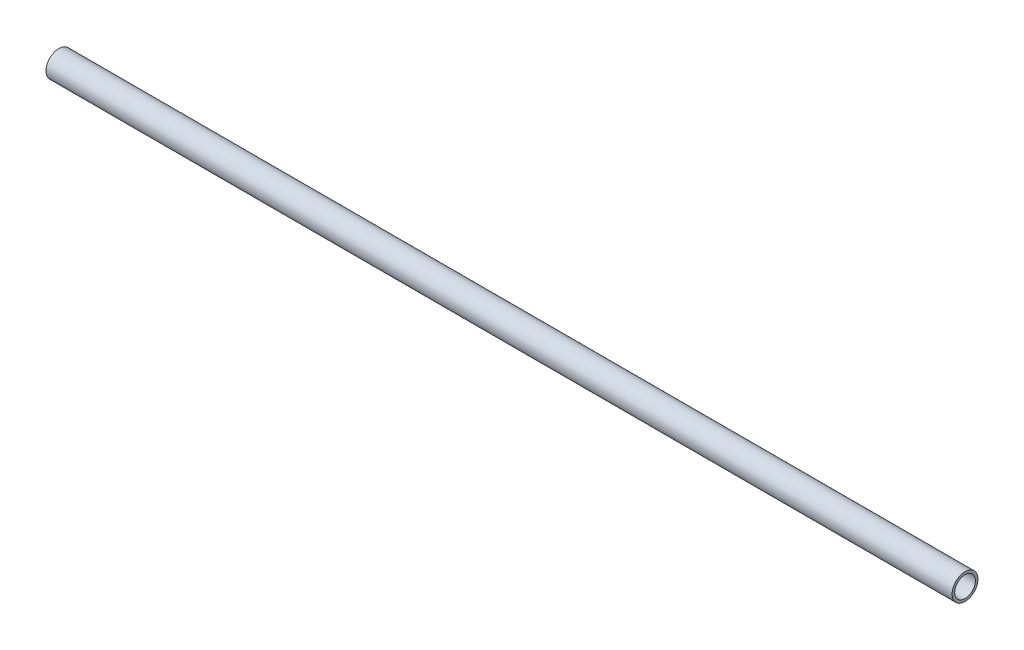
SolidWorks part; units mm, degrees
material "PLA 100% Infill"
ref_plane "Front Plane" through (0, 0, 0) normal (0, 0, 1) x (1, 0, 0)
ref_plane "Top Plane" through (0, 0, 0) normal (0, 1, 0) x (1, 0, 0)
ref_plane "Right Plane" through (0, 0, 0) normal (1, 0, 0) x (0, 0, -1)
sketch "Sketch1" plane through (0, 0, 0) normal (1, 0, 0) x (0, 0, -1)
  circle A0 centre (0, 0) radius 5
  circle A1 centre (0, 0) radius 4
  dimension "D1" = 10
  dimension "1" = 8
extrude "Boss-Extrude1" add sketch "Sketch1" along normal blind 350
